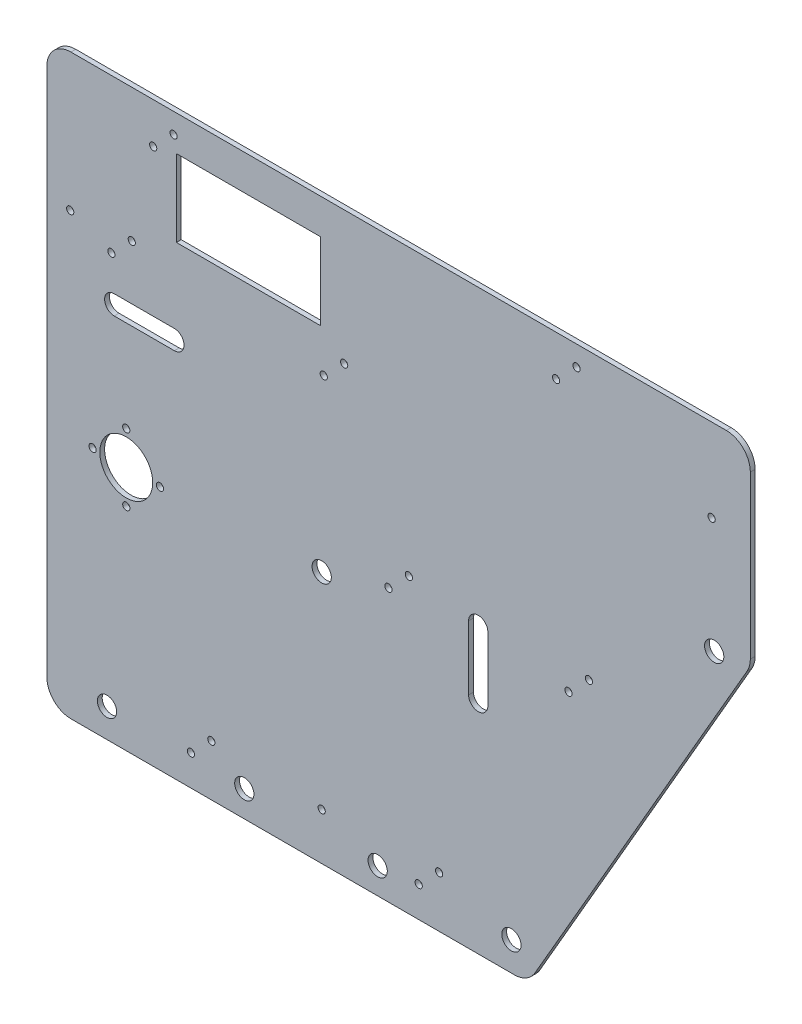
SolidWorks part; units mm, degrees
ref_plane "Front Plane" through (0, 0, 0) normal (0, 0, 1) x (1, 0, 0)
ref_plane "Top Plane" through (0, 0, 0) normal (0, 1, 0) x (1, 0, 0)
ref_plane "Right Plane" through (0, 0, 0) normal (1, 0, 0) x (0, 0, -1)
sketch "Sketch1" plane through (0, 0, 0) normal (0, 0, 1) x (1, 0, 0)
  line L0 (100, 80) -> (192.376, 80)
  line L1 (-100, -80) -> (100, -80)
  line L2 (-100, -80) -> (-100, 80)
  line L3 (-100, 80) -> (100, 80)
  line L4 (100, -80) -> (100, 80)
  line L5 (-100, -80) -> (100, 80) construction
  line L6 (-100, 80) -> (100, -80) construction
  line L7 (192.376, 80) -> (100, -80)
  line L8 (100, 80) -> (100, -80)
  line L10 (-100, 80) -> (192.376, 80)
  line L11 (-100, 80) -> (-100, 110)
  line L12 (-100, 110) -> (192.376, 110)
  line L13 (192.376, 80) -> (192.376, 110)
  point P0 (0, 0)
  dimension "D1" = 160
  dimension "D2" = 200
  dimension "D3" = 30
  dimension "D4" = 30
extrude "Boss-Extrude1" add sketch "Sketch1" along normal blind 2 contours L1 L4 L3 L2 | L7 L0 L4 | L11 L10 L13 L12
sketch "Sketch2" plane through (0, 0, 2) normal (0, 0, 1) x (1, 0, 0)
  line L0 (-100, -80) -> (100, -80) construction
  line L1 (192.376, 80) -> (100, -80) construction
  line L2 (79.2904, 11.2418) -> (79.2904, 37.9086) construction
  line L3 (-100, -80) -> (-100, 110) construction
  line L4 (-72, 78) -> (-47, 78) construction
  line L7 (-100, 110) -> (192.376, 110) construction
  line L8 (75.2904, 11.2418) -> (75.2904, 37.9086)
  line L9 (-72, 82) -> (-47, 82)
  line L10 (-72, 74) -> (-47, 74)
  line L11 (-100, -80) -> (-100, 110) construction
  line L12 (83.2904, 11.2418) -> (83.2904, 37.9086)
  circle A0 centre (93.0718, -68) radius 4
  circle A1 centre (177.3649, 78) radius 4
  circle A2 centre (-67, 22) radius 11
  circle A3 centre (-75, -68) radius 4
  circle A4 centre (-53, 22) radius 1.5
  circle A5 centre (-67, 36) radius 1.5
  circle A6 centre (-81, 22) radius 1.5
  circle A7 centre (-67, 8) radius 1.5
  circle A11 centre (54.5495, -67.2426) radius 1.5
  circle A12 centre (63.0348, -58.7574) radius 1.5
  circle A13 centre (14.2259, -60.5) radius 1.5
  circle A14 centre (-40.1271, -67.2426) radius 1.5
  circle A15 centre (-31.6419, -58.7574) radius 1.5
  circle A16 centre (-90.2956, 102.8814) radius 1.5
  circle A17 centre (-73.1863, 96.1388) radius 1.5
  circle A18 centre (-64.701, 104.6241) radius 1.5
  circle A19 centre (15.0782, 96.1388) radius 1.5
  circle A20 centre (23.5635, 104.6241) radius 1.5
  circle A21 centre (41.9695, 33.1388) radius 1.5
  circle A22 centre (50.4548, 41.6241) radius 1.5
  circle A23 centre (-39.813, 33.1388) radius 1.5 construction
  circle A24 centre (-31.3277, 41.6241) radius 1.5 construction
  circle A25 centre (116.8113, 33.1388) radius 1.5
  circle A26 centre (125.2966, 41.6241) radius 1.5
  circle A27 centre (79.2904, 25) radius 4 construction
  circle A28 centre (14.2259, 25) radius 4
  arc A29 (-72, 82) -> (-72, 74) centre (-72, 78) ccw
  arc A30 (-47, 74) -> (-47, 82) centre (-47, 78) ccw
  circle A31 centre (176.3056, 125.4889) radius 1.5
  arc A32 (75.2904, 11.2418) -> (83.2904, 11.2418) centre (79.2904, 11.2418) ccw
  arc A33 (83.2904, 37.9086) -> (75.2904, 37.9086) centre (79.2904, 37.9086) ccw
  circle A34 centre (-55.8147, 143.1388) radius 1.5
  circle A35 centre (-47.3294, 151.6241) radius 1.5
  circle A36 centre (111.6554, 143.1388) radius 1.5
  circle A37 centre (120.1407, 151.6241) radius 1.5
  circle A38 centre (-17.9479, -69.1174) radius 4
  circle A39 centre (37.4944, -69.1174) radius 4
  point P26 (-59.5, 78)
  point P87 (79.2904, 24.5752)
  dimension "D3" = 8
  dimension "D4" = 8
  dimension "D9" = 22
  dimension "D10" = 8
  dimension "D12" = 3
  dimension "D13" = 3
  dimension "D14" = 3
  dimension "D15" = 3
  dimension "D16" = 14
  dimension "D20" = 8
  dimension "D22" = 4
  dimension "D25" = 3
  dimension "D26" = 3
  dimension "D29" = 8
  dimension "D28" = 3
  dimension "D31" = 8
  dimension "D32" = 8
  dimension "D1" = 12
  dimension "D2" = 12
  dimension "D5" = 32
  dimension "D6" = 12
  dimension "D7" = 88
  dimension "D8" = 33
  dimension "D11" = 12
  dimension "D17" = 14
  dimension "D18" = 14
  dimension "D19" = 14
  dimension "D21" = 85
  dimension "D23" = 28
  dimension "D24" = 25
  dimension "D27" = 25
  dimension "D30" = 8
extrude "Cut-Extrude1" cut sketch "Sketch2" against normal blind 3
sketch "Sketch4" plane through (0, 0, 2) normal (0, 0, 1) x (1, 0, 0)
  line L0 (192.376, 80) -> (192.376, 110) construction
  line L1 (-100, 110) -> (192.376, 110)
  line L2 (-100, 110) -> (-100, 160)
  line L3 (-100, 160) -> (192.376, 160)
  line L4 (192.376, 110) -> (192.376, 160)
  dimension "D1" = 50
extrude "Boss-Extrude2" add sketch "Sketch4" against normal blind 2
fillet "Fillet1" radius 10 5 edges at (192.376, 160, 1) (192.376, 80, 1) (100, -80, 1) (-100, -80, 1) (-100, 160, 1)
sketch "Sketch5" plane through (0, 0, 2) normal (0, 0, 1) x (1, 0, 0)
  line L1 (-46.1781, 113.3814) -> (13.8219, 113.3814)
  line L2 (-46.1781, 113.3814) -> (-46.1781, 145.3814)
  line L3 (-46.1781, 145.3814) -> (13.8219, 145.3814)
  line L4 (13.8219, 113.3814) -> (13.8219, 145.3814)
  circle A2 centre (-55.8147, 143.1388) radius 1.5
  circle A3 centre (-47.3294, 151.6241) radius 1.5
  circle A4 centre (111.6554, 143.1388) radius 1.5
  circle A5 centre (120.1407, 151.6241) radius 1.5
  circle A6 centre (176.3056, 125.4889) radius 1.5
  dimension "D1" = 3
extrude "Cut-Extrude2" cut sketch "Sketch5" against normal blind 11
